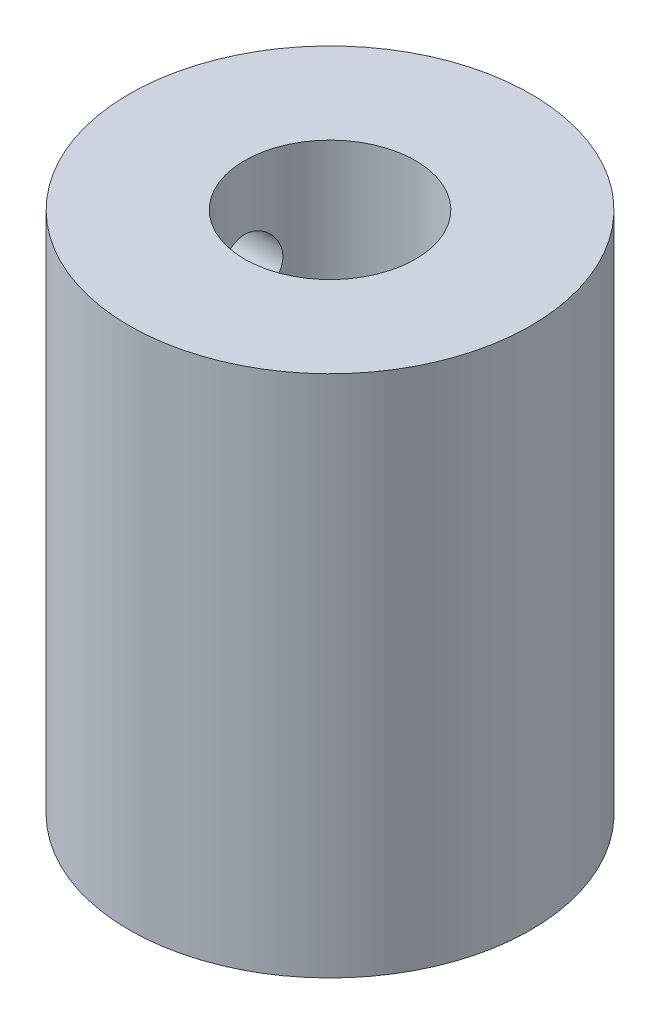
SolidWorks part; units mm, degrees
ref_plane "Front Plane" through (0, 0, 0) normal (0, 0, 1) x (1, 0, 0)
ref_plane "Top Plane" through (0, 0, 0) normal (0, 1, 0) x (1, 0, 0)
ref_plane "Right Plane" through (0, 0, 0) normal (1, 0, 0) x (0, 0, -1)
sketch "Sketch1" plane through (0, 0, 0) normal (0, 1, 0) x (1, 0, 0)
  circle A0 centre (0, 0) radius 9.4
  circle A1 centre (0, 0) radius 4
  dimension "D1" = 18.8
  dimension "D2" = 8
extrude "Boss-Extrude1" add sketch "Sketch1" along normal blind 24.5
sketch "Sketch3" plane through (0, 0, 0) normal (1, 0, 0) x (0, 0, -1)
  line L0 (-9.4, 12.25) -> (9.4, 12.25) construction
  line L1 (-9.4, 24.5) -> (-9.4, 0) construction
  line L2 (9.4, 0) -> (9.4, 24.5) construction
  circle A0 centre (0, 4.5) radius 1.5
  circle A1 centre (0, 20) radius 1.5
  point P8 (0, 0)
  dimension "D1" = 3
  dimension "D2" = 4.5
extrude "Cut-Extrude1" cut sketch "Sketch3" against normal through all
